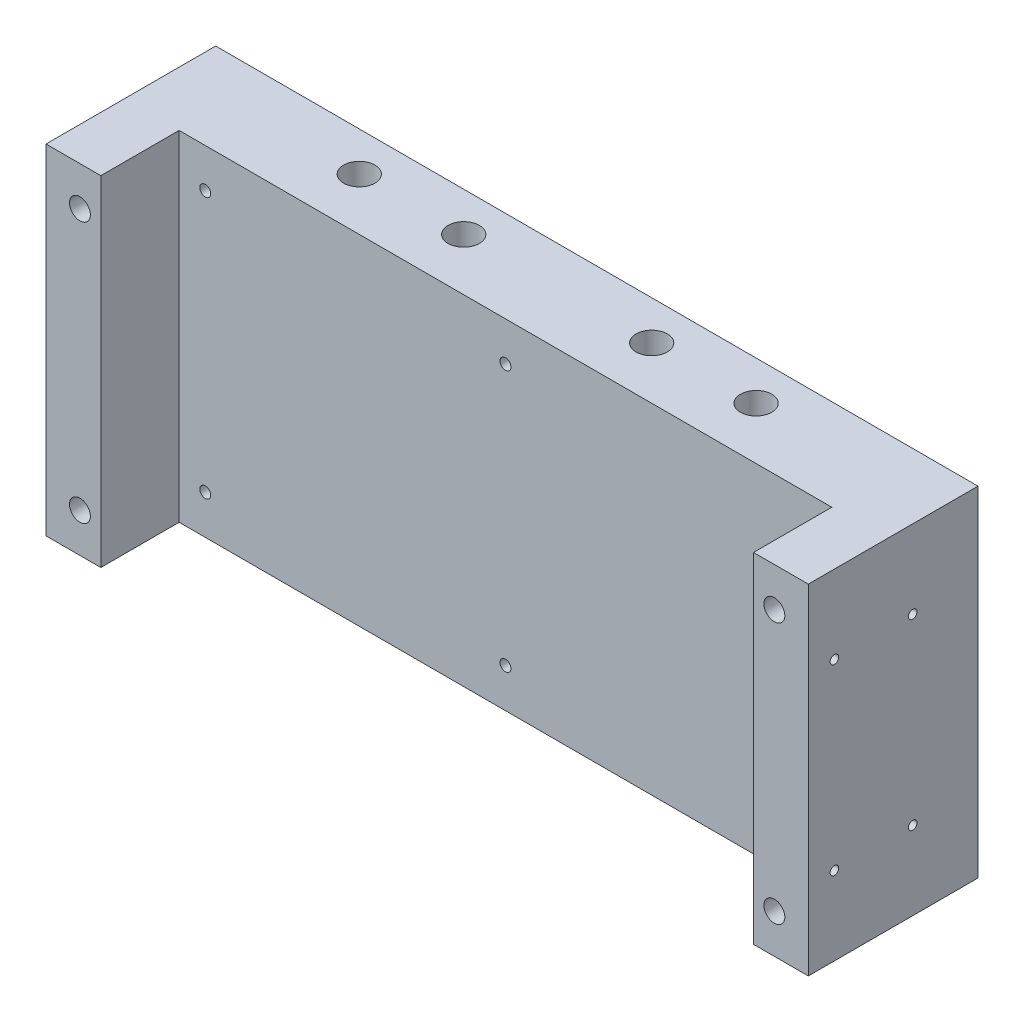
SolidWorks part; units mm, degrees
material "6063-T6"
ref_plane "Front Plane" through (0, 0, 0) normal (0, 0, 1) x (1, 0, 0)
ref_plane "Top Plane" through (0, 0, 0) normal (0, 1, 0) x (1, 0, 0)
ref_plane "Right Plane" through (0, 0, 0) normal (1, 0, 0) x (0, 0, -1)
curve "Curve1"
  spline degree 3 poles (175, 0, 0.3867) (172.0852, 0, 1.0897) (166.2646, 0, 2.4935) (154.6086, 0, 5.0979) (140.0385, 0, 8.0953) (122.5354, 0, 11.2849) (105.0361, 0, 14.0542) (87.5366, 0, 16.3202) (70.0311, 0, 17.9237) (55.4199, 0, 18.4971) (43.7404, 0, 18.2662) (34.9711, 0, 17.6609) (26.1801, 0, 16.4891) (18.8666, 0, 14.8537) (13.0417, 0, 12.9094) (8.568, 0, 10.9324) (4.8344, 0, 8.5605) (1.3476, 0, 5.1921) (-0.8977, 0, 0) (1.3476, 0, -5.1921) (4.8344, 0, -8.5605) (8.568, 0, -10.9324) (13.0417, 0, -12.9094) (18.8666, 0, -14.8537) (26.1801, 0, -16.4891) (34.9711, 0, -17.6609) (43.7404, 0, -18.2662) (55.4199, 0, -18.4971) (70.0311, 0, -17.9237) (87.5366, 0, -16.3202) (105.0361, 0, -14.0542) (122.5354, 0, -11.2849) (140.0385, 0, -8.0953) (154.6086, 0, -5.0979) (166.2646, 0, -2.4935) (172.0852, 0, -1.0897) (175, 0, -0.3867) knots 0 0 0 0 0.024528 0.048982 0.097703 0.146209 0.194518 0.242628 0.290539 0.338289 0.362155 0.386077 0.410161 0.434654 0.447248 0.460338 0.47462 0.483093 0.5 0.516907 0.52538 0.539662 0.552752 0.565346 0.589839 0.613923 0.637845 0.661711 0.709461 0.757372 0.805482 0.853791 0.902297 0.951018 0.975472 1 1 1 1
sketch "Sketch1" plane through (0, 0, 0) normal (0, 1, 0) x (1, 0, 0)
  line L0 (0, 0) -> (-41, 0)
  line L1 (175, 0.3867) -> (175, -0.3867) construction
  line L2 (-41, 0) -> (-41, 65)
  line L3 (-41, 65) -> (251, 65)
  line L4 (251, 65) -> (251, 0)
  line L5 (-41, 0) -> (-41, 5)
  line L6 (251, 0) -> (251, 5)
  line L7 (-41, 5) -> (1.6146, 5)
  line L8 (251, 5) -> (154.8787, 5)
  line L9 (251, 0) -> (175, 0)
  line L11 (251, 65) -> (-41, 65)
  line L12 (251, 65) -> (251, 30)
  line L13 (251, 30) -> (-41, 30)
  line L14 (-41, 65) -> (-41, 30)
  arc A0 (175, 0.3867) -> (175, -0.3867) centre (174.9067, 0) cw
  spline S0 degree 3 poles (991.754, -1812.021) (410.0199, 103.4385) (290.9339, 25.363) (154.6086, -5.0979) (140.0385, -8.0953) (122.5354, -11.2849) (105.0361, -14.0542) (87.5366, -16.3202) (70.0311, -17.9237) (55.4199, -18.4971) (43.7404, -18.2662) (34.9711, -17.6609) (26.1801, -16.4891) (18.8666, -14.8537) (13.0417, -12.9094) (8.568, -10.9324) (4.8344, -8.5605) (1.3476, -5.1921) (-0.8977, 0) (1.3476, 5.1921) (4.8344, 8.5605) (8.568, 10.9324) (13.0417, 12.9094) (18.8666, 14.8537) (26.1801, 16.4891) (34.9711, 17.6609) (43.7404, 18.2662) (55.4199, 18.4971) (70.0311, 17.9237) (87.5366, 16.3202) (105.0361, 14.0542) (122.5354, 11.2849) (140.0385, 8.0953) (154.6086, 5.0979) (290.9339, -25.363) (410.0199, -103.4385) (991.754, 1812.0209) knots -1.045008 -1.045008 -1.045008 -1.045008 0.024528 0.048982 0.097703 0.146209 0.194518 0.242628 0.290539 0.338289 0.362155 0.386077 0.410161 0.434654 0.447248 0.460338 0.47462 0.483093 0.5 0.516907 0.52538 0.539662 0.552752 0.565346 0.589839 0.613923 0.637845 0.661711 0.709461 0.757372 0.805482 0.853791 0.902297 0.951018 0.975472 2.045008 2.045008 2.045008 2.045008 only from (175, -0.3867) to (175, 0.3867) construction
  spline S1 degree 3 poles (175, -0.3867) (172.0852, -1.0897) (166.2646, -2.4935) (154.6086, -5.0979) (140.0385, -8.0953) (122.5354, -11.2849) (105.0361, -14.0542) (87.5366, -16.3202) (70.0311, -17.9237) (55.4199, -18.4971) (43.7404, -18.2662) (34.9711, -17.6609) (26.1801, -16.4891) (18.8666, -14.8537) (13.0417, -12.9094) (8.568, -10.9324) (4.8344, -8.5605) (1.3476, -5.1921) (-0.8977, 0) (1.3476, 5.1921) (4.8344, 8.5605) (8.568, 10.9324) (13.0417, 12.9094) (18.8666, 14.8537) (26.1801, 16.4891) (34.9711, 17.6609) (43.7404, 18.2662) (55.4199, 18.4971) (70.0311, 17.9237) (87.5366, 16.3202) (105.0361, 14.0542) (122.5354, 11.2849) (140.0385, 8.0953) (154.6086, 5.0979) (166.2646, 2.4935) (172.0852, 1.0897) (175, 0.3867) knots 0 0 0 0 0.024528 0.048982 0.097703 0.146209 0.194518 0.242628 0.290539 0.338289 0.362155 0.386077 0.410161 0.434654 0.447248 0.460338 0.47462 0.483093 0.5 0.516907 0.52538 0.539662 0.552752 0.565346 0.589839 0.613923 0.637845 0.661711 0.709461 0.757372 0.805482 0.853791 0.902297 0.951018 0.975472 1 1 1 1
  point P15 (175, 0)
  dimension "D6" = 35
  dimension "D1" = 30
  dimension "D2" = 41
  dimension "D4" = 5
  dimension "D5" = 5
  dimension "D7" = 292
extrude "Boss-Extrude1" add sketch "Sketch1" along normal blind 130 contours L13 L4 L3 L2
sketch "Sketch4" plane through (0, 0, -30) normal (0, 0, 1) x (1, 0, 0)
  line L0 (251, 0) -> (-41, 0) construction
  line L1 (-41, 130) -> (-20, 130)
  line L2 (-41, 130) -> (-41, 0)
  line L3 (-41, 0) -> (-20, 0)
  line L4 (-20, 130) -> (-20, 0)
  line L6 (251, 130) -> (230, 130)
  line L7 (251, 130) -> (251, 0)
  line L8 (251, 0) -> (230, 0)
  line L9 (230, 130) -> (230, 0)
  dimension "D1" = 21
  dimension "D2" = 21
extrude "Boss-Extrude2" add sketch "Sketch4" along normal blind 30
sketch "Sketch2" plane through (0, 0, -65) normal (0, 0, 1) x (1, 0, 0)
  line L0 (251, 130) -> (251, 0) construction
  line L1 (-41, 130) -> (-28, 130) construction
  line L2 (-41, 130) -> (-41, 115) construction
  line L3 (-41, 115) -> (-28, 115) construction
  line L4 (-28, 130) -> (-28, 115) construction
  line L5 (-41, 0) -> (-28, 0) construction
  line L6 (-41, 0) -> (-41, 15) construction
  line L7 (-41, 15) -> (-28, 15) construction
  line L8 (-28, 0) -> (-28, 15) construction
  line L9 (251, 130) -> (238, 130) construction
  line L10 (251, 130) -> (251, 115) construction
  line L11 (251, 115) -> (238, 115) construction
  line L12 (238, 130) -> (238, 115) construction
  line L13 (-41, 0) -> (251, 0) construction
  line L14 (238, 15) -> (251, 15) construction
  line L15 (238, 15) -> (238, 0) construction
  line L16 (238, 0) -> (251, 0) construction
  line L17 (251, 15) -> (251, 0) construction
  circle A0 centre (-28, 115) radius 4
  circle A1 centre (-28, 15) radius 4
  circle A2 centre (238, 115) radius 4
  circle A3 centre (238, 15) radius 4
  dimension "D1" = 13
  dimension "D2" = 15
  dimension "D3" = 15
  dimension "D4" = 13
  dimension "D5" = 13
  dimension "D6" = 15
  dimension "D7" = 13
  dimension "D8" = 15
extrude "Cut-Extrude1" cut sketch "Sketch2" along normal through all contours A2 | A0 | A1 | A3
sketch "Sketch3" plane through (0, 0, -65) normal (0, 0, -1) x (-1, 0, 0)
  line L0 (-60, 65) -> (41, 65)
  line L3 (41, 130) -> (41, 0) construction
  circle A0 centre (-60, 65) radius 8
  point P6 (-87.5, 60)
sketch "Sketch5" plane through (0, 0, -30) normal (0, 0, 1) x (1, 0, 0)
  line L0 (230, 130) -> (-20, 130) construction
  line L1 (-10, 15) -> (220, 15) construction
  line L2 (-10, 15) -> (-10, 115) construction
  line L3 (-10, 115) -> (220, 115) construction
  line L4 (220, 15) -> (220, 115) construction
  line L5 (230, 0) -> (-20, 0) construction
  line L6 (-20, 0) -> (-20, 130) construction
  line L7 (230, 130) -> (230, 0) construction
  dimension "D1" = 15
  dimension "D2" = 15
  dimension "D3" = 10
  dimension "D4" = 10
hole_wizard "M5 Tapped Hole1" positions "Sketch6" profile "Sketch7" tap size "M5" standard "ISO" end condition through all
sketch "Sketch6" plane through (0, 0, -30) normal (0, 0, 1) x (1, 0, 0)
  line L0 (-10, 115) -> (220, 115) construction
  line L1 (-10, 15) -> (220, 15) construction
  point P0 (-10, 115)
  point P3 (105, 115)
  point P7 (220, 115)
  point P10 (220, 15)
  point P13 (105, 15)
  point P17 (-10, 15)
sketch "Sketch7" plane through (-10, 115, -30) normal (1, 0, 0) x (0, -1, 0)
  line L0 (0, 0) -> (0, 35)
  line L1 (0, 35) -> (2.1, 35)
  line L2 (2.1, 35) -> (2.1, 0)
  line L5 (2.1, 0) -> (0, 0)
  line L11 (0, -6.35) -> (0, 107.95) construction
  dimension "Thru Tap Drill Dia." = 4.2
  dimension "Thru Tap Drill Depth" = 35
cosmetic thread "Hole Thread2" parameters "D2"=5
cosmetic thread "Hole Thread5" parameters "D2"=5
cosmetic thread "Hole Thread6" parameters "D2"=5
cosmetic thread "Hole Thread7" parameters "D2"=5
cosmetic thread "Hole Thread8" parameters "D2"=5
cosmetic thread "Hole Thread9" parameters "D2"=5
sketch "Sketch12" plane through (0, 0, -65) normal (0, 0, -1) x (-1, 0, 0)
  line L1 (-235, 125) -> (-214.0746, 125)
  line L2 (-235, 125) -> (-235, 5)
  line L3 (-235, 5) -> (-214.0746, 5)
  line L4 (-214.0746, 125) -> (-214.0746, 5)
  line L6 (70, 5) -> (50, 5)
  line L7 (70, 5) -> (70, 125)
  line L8 (70, 125) -> (50, 125)
  line L9 (50, 5) -> (50, 125)
  line L11 (41, 130) -> (-251, 130) construction
  line L12 (41, 0) -> (-251, 0) construction
  dimension "D1" = 5
  dimension "D2" = 5
  dimension "D3" = 5
  dimension "D4" = 5
sketch "Sketch19" plane through (251, 0, 0) normal (1, 0, 0) x (0, 0, -1)
  line L0 (0, 0) -> (0, 130) construction
  line L1 (10, 30) -> (40, 30)
  line L2 (10, 30) -> (10, 100)
  line L3 (10, 100) -> (40, 100)
  line L4 (40, 30) -> (40, 100)
  line L6 (65, 0) -> (0, 0) construction
  line L7 (65, 130) -> (0, 130) construction
  dimension "D1" = 30
  dimension "D2" = 10
  dimension "D3" = 30
  dimension "D4" = 30
sketch "Sketch20" plane through (-41, 0, 0) normal (-1, 0, 0) x (0, 0, 1)
  line L0 (0, 130) -> (-65, 130) construction
  line L1 (-55, 100) -> (-25, 100)
  line L2 (-55, 100) -> (-55, 30)
  line L3 (-55, 30) -> (-25, 30)
  line L4 (-25, 100) -> (-25, 30)
  line L5 (-65, 130) -> (-65, 0) construction
  line L6 (0, 0) -> (-65, 0) construction
  dimension "D1" = 30
  dimension "D2" = 10
  dimension "D3" = 30
  dimension "D4" = 30
hole_wizard "Tap Drill for M4 Tap1" positions "Sketch26" profile "Sketch27" hole size "M4" standard "ISO"
sketch "Sketch26" plane through (-41, 0, 0) normal (-1, 0, 0) x (0, 0, 1)
  point P0 (-55, 100)
  point P3 (-25, 100)
  point P6 (-55, 30)
  point P9 (-25, 30)
sketch "Sketch27" plane through (-41, 100, -55) normal (0, 1, 0) x (0, 0, 1)
  line L0 (0, 0) -> (0, 6.9914)
  line L1 (0, 6.9914) -> (1.65, 6)
  line L2 (1.65, 6) -> (1.65, 0)
  line L5 (1.65, 0) -> (0, 0)
  line L10 (0, 6.9914) -> (-1.65, 6) construction
  line L11 (0, -6.35) -> (0, 107.95) construction
  dimension "Hole Dia." = 3.3
  dimension "Hole Depth" = 6
  dimension "Drill Angle" = 118
hole_wizard "Tap Drill for M4 Tap2" positions "Sketch28" profile "Sketch29" hole size "M4" standard "ISO"
sketch "Sketch28" plane through (251, 0, 0) normal (1, 0, 0) x (0, 0, -1)
  point P0 (10, 100)
  point P3 (40, 100)
  point P6 (10, 30)
  point P9 (40, 30)
sketch "Sketch29" plane through (251, 100, -10) normal (0, 1, 0) x (0, 0, -1)
  line L0 (0, 0) -> (0, 6.9914)
  line L1 (0, 6.9914) -> (1.65, 6)
  line L2 (1.65, 6) -> (1.65, 0)
  line L5 (1.65, 0) -> (0, 0)
  line L10 (0, 6.9914) -> (-1.65, 6) construction
  line L11 (0, -6.35) -> (0, 107.95) construction
  dimension "Hole Dia." = 3.3
  dimension "Hole Depth" = 6
  dimension "Drill Angle" = 118
sketch "Sketch31" plane through (0, 0, -65) normal (0, 0, -1) x (-1, 0, 0)
  line L0 (-251, 30) -> (-251, 100) construction
  line L1 (-191, 120) -> (-131, 120)
  line L2 (-201, 110) -> (-201, 20)
  line L3 (-191, 10) -> (-131, 10)
  line L4 (-121, 110) -> (-121, 20)
  line L5 (-79, 120) -> (-19, 120)
  line L6 (-89, 110) -> (-89, 20)
  line L7 (-79, 10) -> (-19, 10)
  line L8 (-9, 110) -> (-9, 20)
  line L9 (41, 100) -> (41, 30) construction
  line L10 (41, 130) -> (-251, 130) construction
  line L11 (-175, 0) -> (0, 0) construction
  arc A0 (-19, 120) -> (-9, 110) centre (-19, 110) cw
  arc A1 (-79, 120) -> (-89, 110) centre (-79, 110) ccw
  arc A2 (-89, 20) -> (-79, 10) centre (-79, 20) ccw
  arc A3 (-19, 10) -> (-9, 20) centre (-19, 20) ccw
  arc A4 (-201, 20) -> (-191, 10) centre (-191, 20) ccw
  arc A5 (-131, 10) -> (-121, 20) centre (-131, 20) ccw
  arc A6 (-131, 120) -> (-121, 110) centre (-131, 110) cw
  arc A7 (-191, 120) -> (-201, 110) centre (-191, 110) ccw
  dimension "D9" = 10
  dimension "D1" = 50
  dimension "D2" = 50
  dimension "D3" = 80
  dimension "D4" = 10
  dimension "D5" = 10
  dimension "D6" = 10
  dimension "D7" = 10
  dimension "D8" = 80
extrude "Cut-Extrude2" cut sketch "Sketch31" against normal offset from surface (30 mm away) 5 up to face at (-7.9, 115, -30)
sketch "Sketch32" plane through (0, 10, 0) normal (0, 1, 0) x (1, 0, 0)
  line L0 (-41, 0) -> (-41, 65) construction
  line L1 (-41, 65) -> (251, 65) construction
  line L2 (251, 65) -> (251, 0) construction
  point P0 (29, 50)
  point P1 (69, 50)
  point P2 (141, 50)
  point P3 (181, 50)
  dimension "D1" = 70
  dimension "D2" = 40
  dimension "D3" = 70
  dimension "D4" = 40
  dimension "D5" = 15
hole_wizard "Ø12.0mm Dowel Hole1" positions "Sketch33" profile "Sketch34" hole size "Ø12.0" standard "ISO"
sketch "Sketch33" plane through (0, 130, 0) normal (0, 1, 0) x (1, 0, 0)
  point P0 (29, 50)
  point P3 (69, 50)
  point P6 (141, 50)
  point P9 (181, 50)
sketch "Sketch34" plane through (29, 130, -50) normal (1, 0, 0) x (0, 0, 1)
  line L0 (0, 0) -> (0, 13.6052)
  line L1 (0, 13.6052) -> (6, 10)
  line L2 (6, 10) -> (6, 0)
  line L5 (6, 0) -> (0, 0)
  line L10 (0, 13.6052) -> (-6, 10) construction
  line L11 (0, -6.35) -> (0, 107.95) construction
  dimension "Hole Dia." = 12
  dimension "Hole Depth" = 10
  dimension "Drill Angle" = 118
hole_wizard "Ø8.0mm Dowel Hole1" positions "Sketch35" profile "Sketch36" hole size "Ø8.0" standard "ISO"
sketch "Sketch35" plane through (0, 10, 0) normal (0, 1, 0) x (1, 0, 0)
  point P0 (69, 50)
  point P3 (29, 50)
  point P6 (141, 50)
  point P9 (181, 50)
sketch "Sketch36" plane through (69, 10, -50) normal (1, 0, 0) x (0, 0, 1)
  line L0 (0, 0) -> (0, 12.4034)
  line L1 (0, 12.4034) -> (4, 10)
  line L2 (4, 10) -> (4, 0)
  line L5 (4, 0) -> (0, 0)
  line L10 (0, 12.4034) -> (-4, 10) construction
  line L11 (0, -6.35) -> (0, 107.95) construction
  dimension "Hole Dia." = 8
  dimension "Hole Depth" = 10
  dimension "Drill Angle" = 118
